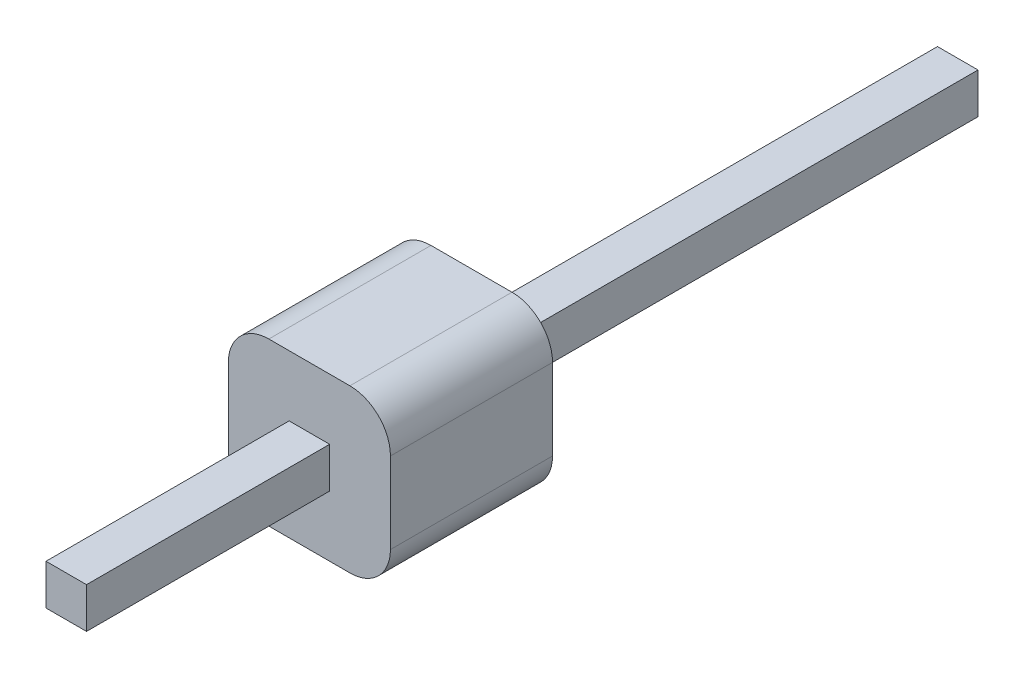
SolidWorks part; units mm, degrees
ref_plane "前视基准面" through (0, 0, 0) normal (0, 0, 1) x (1, 0, 0)
ref_plane "上视基准面" through (0, 0, 0) normal (0, 1, 0) x (1, 0, 0)
ref_plane "右视基准面" through (0, 0, 0) normal (1, 0, 0) x (0, 0, -1)
sketch "草图1" plane through (0, 0, 0) normal (0, 0, 1) x (1, 0, 0)
  line L0 (0, 5.3599) -> (0, -8.0108) construction
  line L1 (-1, 1) -> (1, 1)
  line L2 (-1, 1) -> (-1, -1)
  line L3 (-1, -1) -> (1, -1)
  line L4 (1, 1) -> (1, -1)
  line L5 (-4.807, 0) -> (4.5413, 0) construction
  dimension "D1" = 2
  dimension "D2" = 2
extrude "拉伸1" add sketch "草图1" along normal blind 2
ref_plane "基准面1" through (0, 0, 5) normal (0, 0, -1) x (-1, 0, 0)
sketch "草图2" plane through (0, 0, 5) normal (0, 0, -1) x (-1, 0, 0)
  line L0 (-1, 0) -> (1, 0) construction
  line L1 (-1, -1) -> (-1, 1) construction
  line L2 (1, 1) -> (1, -1) construction
  line L3 (0, 1.9407) -> (0, -4.2425) construction
  line L5 (-0.25, 0.25) -> (0.25, 0.25)
  line L6 (-0.25, 0.25) -> (-0.25, -0.25)
  line L7 (-0.25, -0.25) -> (0.25, -0.25)
  line L8 (0.25, 0.25) -> (0.25, -0.25)
  dimension "D1" = 0.5
  dimension "D2" = 0.5
sketch "草图3" plane through (0, 0, 0) normal (1, 0, 0) x (0, 0, -1)
  line L0 (6, -0.28) -> (-5.08, -0.28)
  line L1 (-5, 1.9407) -> (-5, -4.2425) construction
  line L8 (-2, 1) -> (0, 1) construction
  line L9 (0, -1) -> (0, 1) construction
  point P11 (2.54, -1.2991)
  dimension "D1" = 5.08
  dimension "D2" = 11
  dimension "D4" = 1.28
sweep "扫描1" add profiles "草图2" path "草图3"
fillet "圆角1" radius 0.5 4 edges at (1, 1, 1) (1, -1, 1) (-1, -1, 1) (-1, 1, 1)
